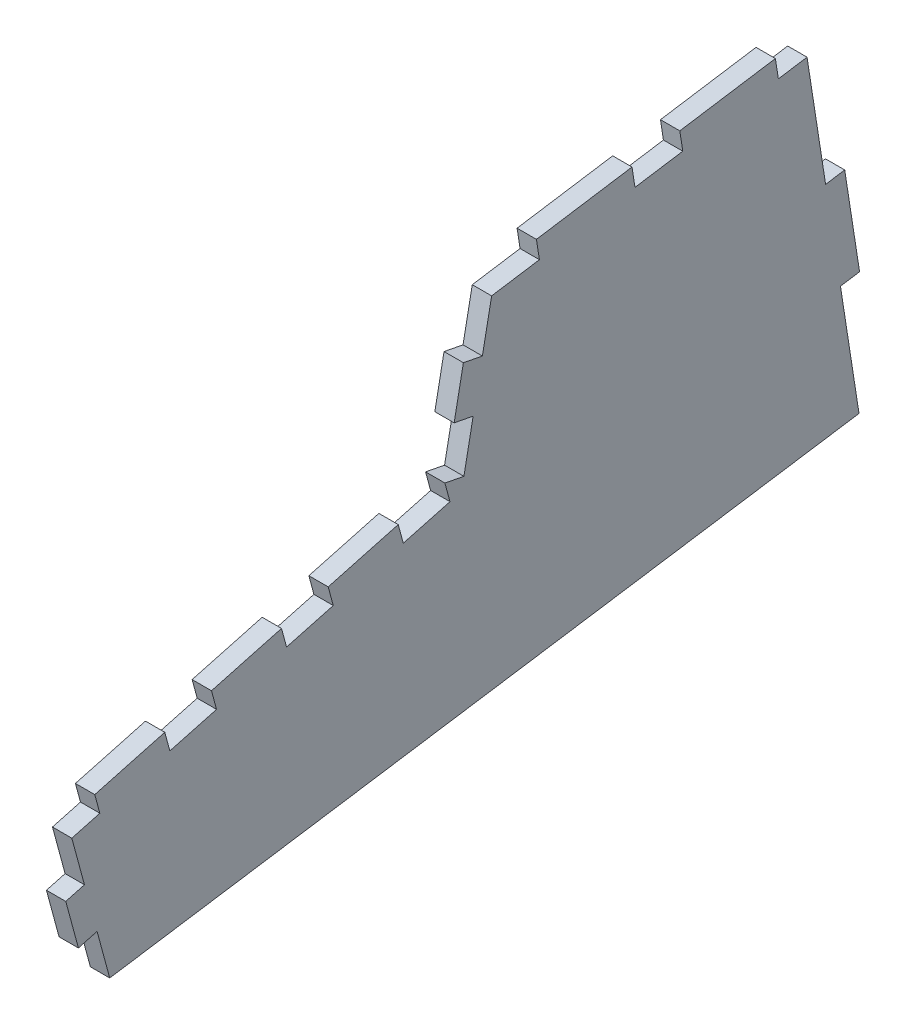
SolidWorks part; units mm, degrees
ref_plane "Front Plane" through (0, 0, 0) normal (0, 0, 1) x (1, 0, 0)
ref_plane "Top Plane" through (0, 0, 0) normal (0, 1, 0) x (1, 0, 0)
ref_plane "Right Plane" through (0, 0, 0) normal (1, 0, 0) x (0, 0, -1)
sketch3d "3DSketch1"
  line L0 (-135.3194, -27.3996, -28.1631) -> (-135.3194, -2.6959, -24.3251)
  line L1 (-135.3194, -2.6959, -24.3251) -> (-135.3194, -2.0818, -28.2777)
  line L2 (-135.3194, -2.0818, -28.2777) -> (-135.3194, 17.6811, -25.2073)
  line L3 (-135.3194, 17.6811, -25.2073) -> (-135.3194, 17.067, -21.2547)
  line L4 (-135.3194, 17.067, -21.2547) -> (-135.3194, 41.7706, -17.4166)
  line L5 (-135.3194, 41.7706, -17.4166) -> (-135.3194, 40.8495, -11.4878)
  line L6 (-135.3194, 40.8495, -11.4878) -> (-135.3194, 44.8021, -10.8737)
  line L7 (-135.3194, 44.8021, -10.8737) -> (-135.3194, 41.7316, 8.8892)
  line L8 (-135.3194, 41.7316, 8.8892) -> (-135.3194, 37.7791, 8.2751)
  line L9 (-135.3194, 37.7791, 8.2751) -> (-135.3194, 36.2438, 18.1566)
  line L10 (-135.3194, 36.2438, 18.1566) -> (-135.3194, 40.1964, 18.7707)
  line L11 (-135.3194, 40.1964, 18.7707) -> (-135.3194, 37.126, 38.5336)
  line L12 (-135.3194, 37.126, 38.5336) -> (-135.3194, 33.1734, 37.9195)
  line L13 (-135.3194, 33.1734, 37.9195) -> (-135.3194, 31.6382, 47.8009)
  line L14 (-135.3194, 31.6382, 47.8009) -> (-135.3194, 21.8223, 49.7108)
  line L15 (-135.3194, 21.8223, 49.7108) -> (-135.3194, 22.5862, 53.6371)
  line L16 (-135.3194, 22.5862, 53.6371) -> (-135.3194, 12.7703, 55.5469)
  line L17 (-135.3194, 12.7703, 55.5469) -> (-135.3194, 12.0063, 51.6206)
  line L18 (-135.3194, 12.0063, 51.6206) -> (-135.3194, 2.1904, 53.5304)
  line L19 (-135.3194, 2.1904, 53.5304) -> (-135.3194, 2.9543, 57.4568)
  line L20 (-135.3194, 2.9543, 57.4568) -> (-135.3194, -0.9068, 56.4119)
  line L21 (-135.3194, -0.9068, 56.4119) -> (-135.3194, -3.519, 66.0646)
  line L22 (-135.3194, -3.519, 66.0646) -> (-135.3194, 0.3421, 67.1095)
  line L23 (-135.3194, 0.3421, 67.1095) -> (-135.3194, -3.5763, 81.5887)
  line L24 (-135.3194, -3.5763, 81.5887) -> (-135.3194, -7.4374, 80.5438)
  line L25 (-135.3194, -7.4374, 80.5438) -> (-135.3194, -10.0496, 90.1966)
  line L26 (-135.3194, -10.0496, 90.1966) -> (-135.3194, -6.1885, 91.2415)
  line L27 (-135.3194, -6.1885, 91.2415) -> (-135.3194, -10.1069, 105.7207)
  line L28 (-135.3194, -10.1069, 105.7207) -> (-135.3194, -13.968, 104.6758)
  line L29 (-135.3194, -13.968, 104.6758) -> (-135.3194, -16.5803, 114.3285)
  line L30 (-135.3194, -16.5803, 114.3285) -> (-135.3194, -12.7191, 115.3734)
  line L31 (-135.3194, -12.7191, 115.3734) -> (-135.3194, -16.6375, 129.8526)
  line L32 (-135.3194, -16.6375, 129.8526) -> (-135.3194, -20.4986, 128.8077)
  line L33 (-135.3194, -20.4986, 128.8077) -> (-135.3194, -22.066, 134.5994)
  line L34 (-135.3194, -22.066, 134.5994) -> (-135.3194, -31.7187, 131.9871)
  line L35 (-135.3194, -31.7187, 131.9871) -> (-135.3194, -32.7636, 135.8483)
  line L36 (-135.3194, -32.7636, 135.8483) -> (-135.3194, -42.4164, 133.236)
  line L37 (-135.3194, -42.4164, 133.236) -> (-135.3194, -41.3715, 129.3749)
  line L38 (-135.3194, -41.3715, 129.3749) -> (-135.3194, -51.0243, 126.7627)
  line L39 (-135.3194, -51.0243, 126.7627) -> (-135.3194, -27.3996, -28.1631)
extrude "Boss-Extrude2" add sketch "3DSketch1" along direction (1, 0, 0) on the side against the normal blind 4
